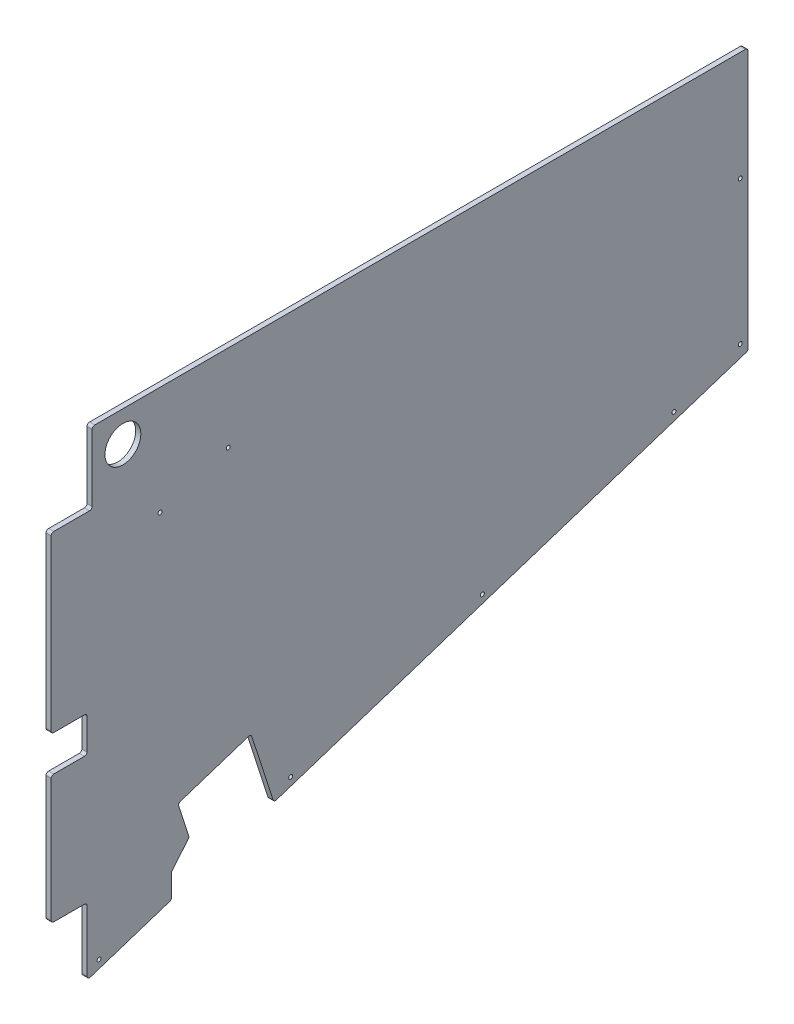
SolidWorks part; units mm, degrees
material "PC High Viscosity"
ref_plane "Front Plane" through (0, 0, 0) normal (0, 0, 1) x (1, 0, 0)
ref_plane "Top Plane" through (0, 0, 0) normal (0, 1, 0) x (1, 0, 0)
ref_plane "Right Plane" through (0, 0, 0) normal (1, 0, 0) x (0, 0, -1)
sketch "Sketch1" plane through (0, 0, 0) normal (1, 0, 0) x (0, 0, -1)
  line L0 (1016, 533.4) -> (1066.8, 533.4)
  line L1 (0, 0) -> (1066.8, 0)
  line L2 (0, 0) -> (0, 533.4)
  line L3 (0, 533.4) -> (50.8, 533.4)
  line L4 (1066.8, 0) -> (1066.8, 533.4)
  line L6 (50.8, 533.4) -> (50.8, 622.3)
  line L8 (1016, 533.4) -> (1016, 622.3)
  line L13 (50.8, 622.3) -> (1016, 622.3)
  dimension "D1" = 1066.8
  dimension "D2" = 533.4
  dimension "D3" = 50.8
  dimension "D4" = 50.8
  dimension "D5" = 88.9
  dimension "D6" = 965.2
extrude "Boss-Extrude1" add sketch "Sketch1" along normal blind 6.35
sketch "Sketch2" plane through (6.35, 0, 0) normal (1, 0, 0) x (0, 0, -1)
  line L1 (0, 0) -> (1066.8, 0) construction
  line L2 (149.225, 95.25) -> (171.0336, 121.2405)
  line L3 (171.0336, 121.2405) -> (157.0619, 164.2411)
  line L4 (157.0619, 164.2411) -> (247.65, 193.675)
  line L5 (247.65, 193.675) -> (276.0453, 106.2834)
  line L7 (0, 533.4) -> (0, 0) construction
  line L9 (863.6, 297.1915) -> (863.6, 622.3)
  line L10 (1016, 622.3) -> (50.8, 622.3) construction
  line L11 (863.6, 622.3) -> (1016, 622.3)
  line L12 (1016, 622.3) -> (1016, 533.4)
  line L13 (1016, 533.4) -> (1066.8, 533.4)
  line L14 (1066.8, 533.4) -> (1066.8, 0)
  line L15 (1066.8, 0) -> (0, 0)
  line L16 (50.8, 622.3) -> (50.8, 533.4) construction
  line L17 (0, 114.3) -> (44.45, 114.3)
  line L18 (0, 114.3) -> (0, 0)
  line L20 (44.45, 114.3) -> (44.45, 31.0335)
  line L21 (59.3115, 45.8775) -> (771.9221, 277.4187) construction
  line L22 (276.0453, 106.2834) -> (863.6, 297.1915)
  line L23 (149.225, 95.25) -> (149.225, 65.077)
  line L24 (149.225, 65.077) -> (44.45, 31.0335)
  line L26 (134.9375, 487.7489) -> (219.4864, 515.2205) construction
  line L27 (0, 317.5) -> (44.45, 317.5)
  line L28 (0, 317.5) -> (0, 273.05)
  line L29 (0, 273.05) -> (44.45, 273.05)
  line L30 (44.45, 317.5) -> (44.45, 273.05)
  circle A0 centre (59.3115, 45.8775) radius 2.4575
  circle A1 centre (296.8457, 123.057) radius 2.4574
  circle A2 centre (534.3799, 200.2365) radius 2.4575
  circle A3 centre (771.9221, 277.4187) radius 2.4575
  circle A4 centre (854.075, 309.0545) radius 2.4575
  circle A5 centre (854.075, 486.8545) radius 2.4575
  circle A6 centre (219.4864, 515.2205) radius 2.4574
  circle A7 centre (134.9375, 487.7489) radius 2.4575
  circle A8 centre (88.9, 584.2) radius 22.225
  dimension "D19" = 134.9375
  dimension "D23" = 4.9149
  dimension "D32" = 44.45
  dimension "D33" = 203.2
  dimension "D10" = 249.7582
  dimension "D11" = 249.7667
  dimension "D14" = 9.525
  dimension "D2" = 95.25
  dimension "D4" = 18
  dimension "D5" = 193.675
  dimension "D6" = 247.65
  dimension "D7" = 249.7582
  dimension "D8" = 45.8775
  dimension "D9" = 59.3115
  dimension "D12" = 122
  dimension "D13" = 9.525
  dimension "D15" = 9.525
  dimension "D16" = 854.075
  dimension "D17" = 486.8545
  dimension "D18" = 309.0545
  dimension "D20" = 396.875
  dimension "D21" = 88.9
  dimension "D24" = 149.225
  dimension "D25" = 95.25
  dimension "D26" = 44.45
  dimension "D27" = 114.3
  dimension "D28" = 44.45
  dimension "D29" = 44.45
  dimension "D30" = 38.1
  dimension "D31" = 38.1
extrude "Cut-Extrude1" cut sketch "Sketch2" against normal through all
fillet "Fillet1" radius 3.175 18 edges at (3.175, 164.2411, -157.0619) (3.175, 193.675, -247.65) (3.175, 121.2405, -171.0336) (3.175, 95.25, -149.225) (3.175, 533.4, 0) (3.175, 533.4, -50.8) (3.175, 622.3, -50.8) (3.175, 622.3, -863.6) (3.175, 114.3, -44.45) (3.175, 114.3, 0) (3.175, 106.2834, -276.0453) (3.175, 297.1915, -863.6) (3.175, 65.077, -149.225) (3.175, 31.0335, -44.45) (3.175, 317.5, 0) (3.175, 317.5, -44.45) (3.175, 273.05, -44.45) (3.175, 273.05, 0)
